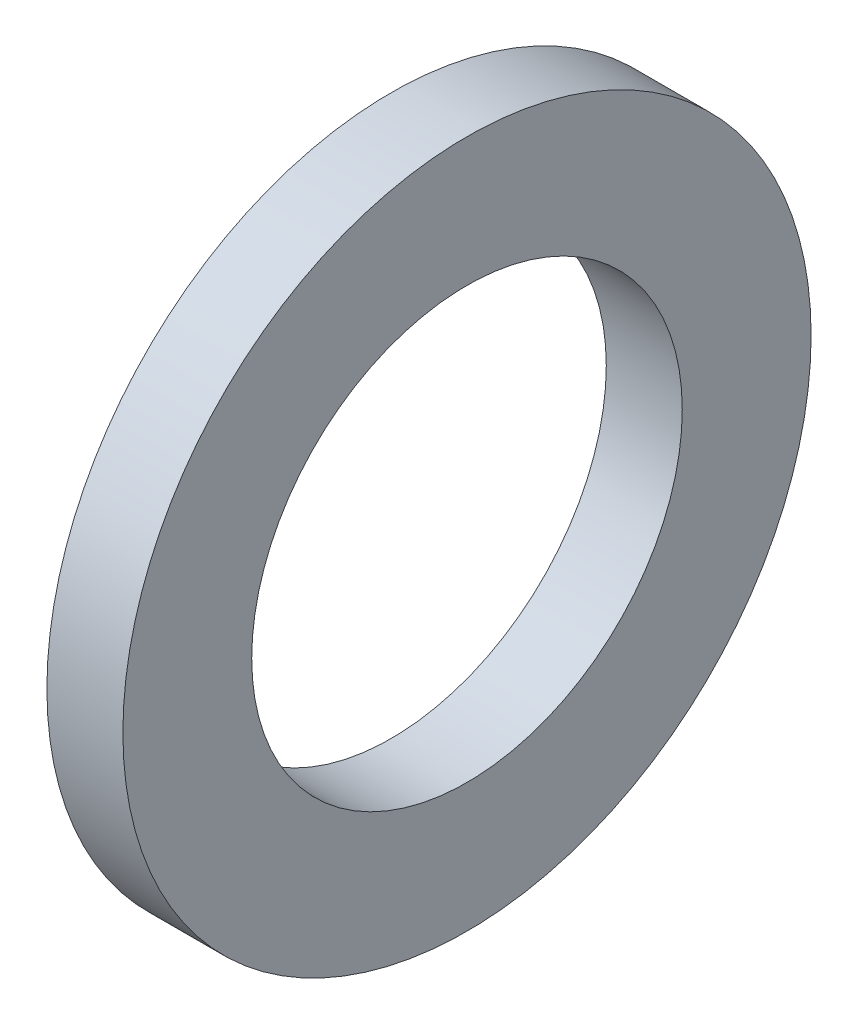
SolidWorks part; units mm, degrees
ref_plane "Front Plane" through (0, 0, 0) normal (0, 0, 1) x (1, 0, 0)
ref_plane "Top Plane" through (0, 0, 0) normal (0, 1, 0) x (1, 0, 0)
ref_plane "Right Plane" through (0, 0, 0) normal (1, 0, 0) x (0, 0, -1)
sketch "Sketch1" plane through (0, 0, 0) normal (1, 0, 0) x (0, 0, -1)
  circle A0 centre (0, 0) radius 7.9375
  circle A1 centre (0, 0) radius 4.9657
  dimension "OD" = 15.875
  dimension "ID" = 9.9314
extrude "Boss-Extrude1" add sketch "Sketch1" along normal blind 1.7526
